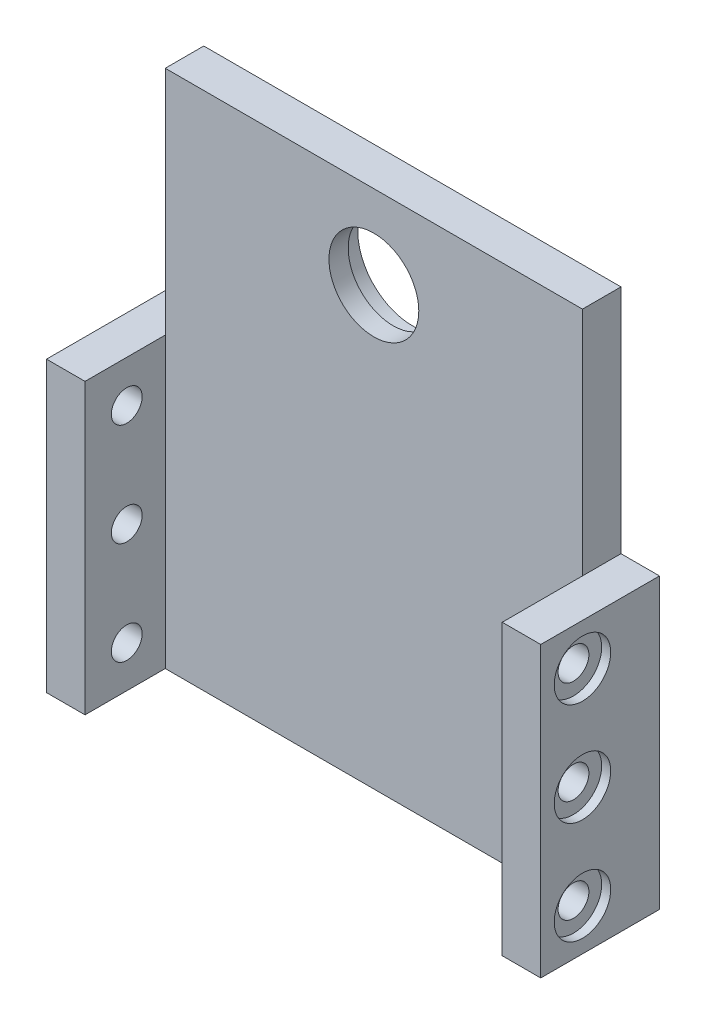
SolidWorks part; units mm, degrees
ref_plane "Plano frontal" through (0, 0, 0) normal (0, 0, 1) x (1, 0, 0)
ref_plane "Plano superior" through (0, 0, 0) normal (0, 1, 0) x (1, 0, 0)
ref_plane "Plano direito" through (0, 0, 0) normal (1, 0, 0) x (0, 0, -1)
sketch "Esboço1" plane through (0, 0, 0) normal (0, 0, 1) x (1, 0, 0)
  line L0 (16, -4.75) -> (16, -11.25) construction
  line L1 (16.25, -11.25) -> (-16.25, -11.25)
  line L2 (16.25, -11.25) -> (16.25, 29.25)
  line L3 (16.25, 29.25) -> (-16.25, 29.25)
  line L4 (-16.25, -11.25) -> (-16.25, 29.25)
  line L5 (-16, -11.25) -> (-16, -4.75) construction
  line L8 (-16.5, -11.25) -> (-10.25, -11.25) construction
  line L10 (-11, 29.25) -> (11, 29.25) construction
  dimension "D1" = 0.25
  dimension "D2" = 0.25
extrude "Ressalto-extrusão1" add sketch "Esboço1" against normal blind 3
sketch "Esboço4" plane through (-16.25, 0, 0) normal (-1, 0, 0) x (0, 0, 1)
  line L1 (-3, -11.25) -> (6.25, -11.25)
  line L2 (-3, -11.25) -> (-3, 11.25)
  line L3 (-3, 11.25) -> (6.25, 11.25)
  line L4 (6.25, -11.25) -> (6.25, 11.25)
  line L5 (6.5, -8.3463) -> (6.5, 13.8) construction
  line L6 (26.75, 11.25) -> (71.25, 11.25) construction
  dimension "D1" = 0.25
extrude "Ressalto-extrusão2" add sketch "Esboço4" along normal blind 3
mirror "Espelhar1" about plane through (0, 0, 0) normal (1, 0, 0) of "Ressalto-extrusão2"
sketch "Esboço5" plane through (0, 0, -3) normal (0, 0, -1) x (-1, 0, 0)
  circle A3 centre (0, 22.75) radius 4.25
  circle A4 centre (0, 22.75) radius 4 construction
  dimension "D1" = 0.25
extrude "Corte-extrusão1" cut sketch "Esboço5" against normal offset from surface (1.5 mm away) 1.5 up to face at (0, 9.75, 0)
sketch "Esboço6" plane through (0, 0, -3) normal (0, 0, -1) x (-1, 0, 0)
  circle A2 centre (0, 22.75) radius 3.5
  circle A3 centre (0, 22.75) radius 2.25 construction
  circle A5 centre (0, 22.75) radius 3.25 construction
  dimension "D1" = 0.25
extrude "Corte-extrusão2" cut sketch "Esboço6" against normal through all
hole_wizard "Rebaixo para parafuso com cabeça redonda de M21" positions "Esboço7" profile "Esboço8" counterbore size "M2" standard "DIN"
sketch "Esboço7" plane through (-19.25, 0, 0) normal (-1, 0, 0) x (0, 0, 1)
  circle A0 centre (3, 8) radius 1.25 construction
  point P0 (3, 8)
  point P6 (3, 0)
  point P9 (3, -8)
  point P15 (0, 0)
sketch "Esboço8" plane through (-19.25, 8, 3) normal (0, 1, 0) x (0, 0, 1)
  line L0 (0, 0) -> (0, 3)
  line L1 (0, 3) -> (1.2, 3)
  line L3 (1.2, 3) -> (1.2, 0.7)
  line L4 (1.2, 0.7) -> (2.2, 0.7)
  line L5 (2.2, 0.7) -> (2.2, 0)
  line L7 (2.2, 0) -> (0, 0)
  line L11 (0, -6.35) -> (0, 107.95) construction
  dimension "Thru Hole Dia." = 2.4
  dimension "Thru Hole Depth" = 3
  dimension "C'Bore Dia." = 4.4
  dimension "C'Bore Depth" = 0.7
mirror "Espelhar3" about plane through (0, 0, 0) normal (1, 0, 0) of "Rebaixo para parafuso com cabeça redonda de M21"
